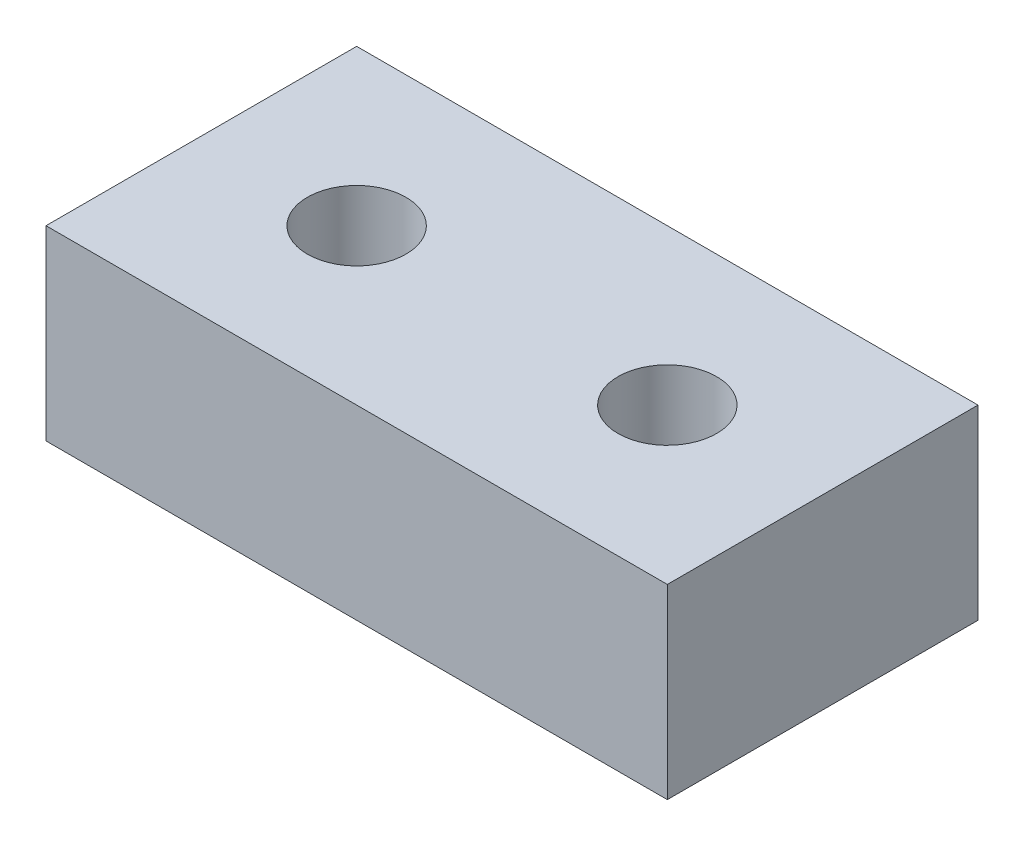
SolidWorks part; units mm, degrees
ref_plane "Front Plane" through (0, 0, 0) normal (0, 0, 1) x (1, 0, 0)
ref_plane "Top Plane" through (0, 0, 0) normal (0, 1, 0) x (1, 0, 0)
ref_plane "Right Plane" through (0, 0, 0) normal (1, 0, 0) x (0, 0, -1)
sketch "Sketch1" plane through (0, 0, 0) normal (0, 1, 0) x (1, 0, 0)
  line L0 (-10, 0) -> (10, 0) construction
  line L1 (-10, 5) -> (10, 5)
  line L2 (-10, 5) -> (-10, -5)
  line L3 (-10, -5) -> (10, -5)
  line L4 (10, 5) -> (10, -5)
  line L5 (-10, 5) -> (10, -5) construction
  line L6 (-10, -5) -> (10, 5) construction
  line L7 (0, 5) -> (0, -5)
  line L8 (0, 5) -> (-10, 0)
  line L9 (-5, 2.5) -> (-5, -5)
  circle A0 centre (-5, 0) radius 1.5875
  circle A1 centre (5, 0) radius 1.5875
  point P0 (0, 0)
  dimension "D3" = 3.175
  dimension "D1" = 20
  dimension "D2" = 10
extrude "Boss-Extrude1" add sketch "Sketch1" along normal blind 6 contours A0 L9 L3 L7 L8 | A0 L9 L8 L2 L3 | L8 L1 L2 | L1 L7 L3 L4 A1
